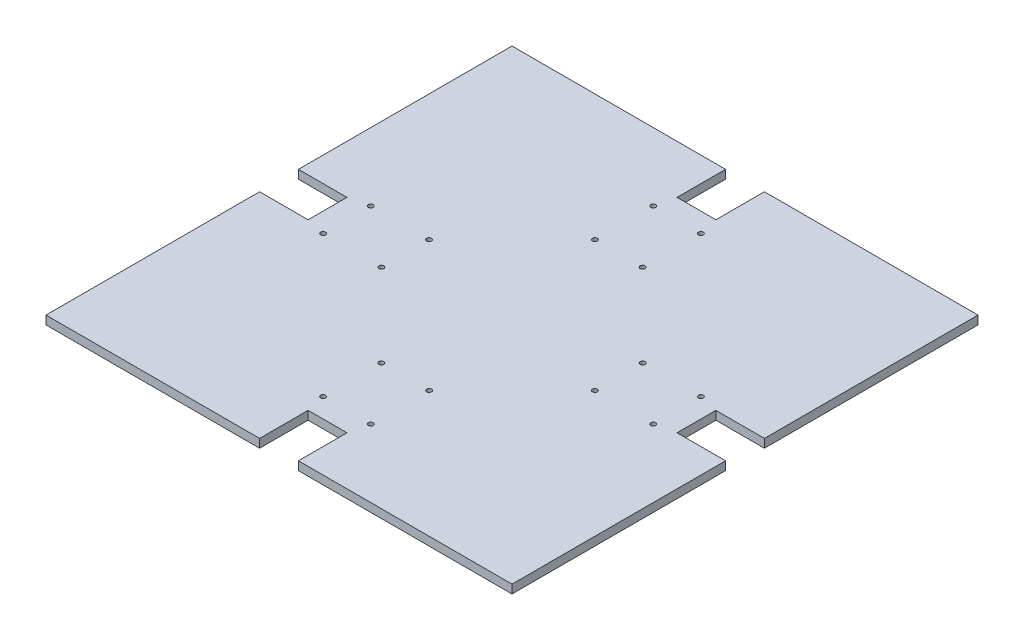
SolidWorks part; units mm, degrees
ref_plane "Front Plane" through (0, 0, 0) normal (0, 0, 1) x (1, 0, 0)
ref_plane "Top Plane" through (0, 0, 0) normal (0, 1, 0) x (1, 0, 0)
ref_plane "Right Plane" through (0, 0, 0) normal (1, 0, 0) x (0, 0, -1)
sketch "Sketch1" plane through (0, 0, 0) normal (0, 1, 0) x (1, 0, 0)
  line L0 (0, 152.4) -> (152.4, 0) construction
  line L1 (-152.4, 152.4) -> (152.4, 152.4)
  line L2 (-152.4, 152.4) -> (-152.4, -152.4)
  line L3 (-152.4, -152.4) -> (152.4, -152.4)
  line L4 (152.4, 152.4) -> (152.4, -152.4)
  line L5 (-152.4, 152.4) -> (152.4, -152.4) construction
  line L6 (-152.4, -152.4) -> (152.4, 152.4) construction
  line L7 (152.4, 0) -> (0, -152.4) construction
  line L8 (0, -152.4) -> (-152.4, 0) construction
  line L9 (-152.4, 0) -> (0, 152.4) construction
  point P0 (0, 0)
  dimension "D1" = 304.8
  dimension "D2" = 304.8
  dimension "D3" = 215.5261
extrude "Boss-Extrude1" add sketch "Sketch1" along normal blind 5.588
sketch "Sketch2" plane through (0, 5.588, 0) normal (0, 1, 0) x (1, 0, 0)
  line L0 (0, 152.4) -> (0, -152.4) construction
  line L1 (-107.95, 15.6) -> (-69.85, 15.6) construction
  line L2 (-107.95, 15.6) -> (-107.95, -15.6) construction
  line L3 (-107.95, -15.6) -> (-69.85, -15.6) construction
  line L4 (-69.85, 15.6) -> (-69.85, -15.6) construction
  line L5 (-107.95, 15.6) -> (-69.85, -15.6) construction
  line L6 (-107.95, -15.6) -> (-69.85, 15.6) construction
  line L7 (-15.6, 107.95) -> (15.6, 107.95) construction
  line L8 (-15.6, 107.95) -> (-15.6, 69.85) construction
  line L9 (-15.6, 69.85) -> (15.6, 69.85) construction
  line L10 (15.6, 107.95) -> (15.6, 69.85) construction
  line L11 (-15.6, 107.95) -> (15.6, 69.85) construction
  line L12 (-15.6, 69.85) -> (15.6, 107.95) construction
  line L13 (-15.6, -69.85) -> (15.6, -69.85) construction
  line L14 (-15.6, -69.85) -> (-15.6, -107.95) construction
  line L15 (-15.6, -107.95) -> (15.6, -107.95) construction
  line L16 (15.6, -69.85) -> (15.6, -107.95) construction
  line L17 (-15.6, -69.85) -> (15.6, -107.95) construction
  line L18 (-15.6, -107.95) -> (15.6, -69.85) construction
  line L19 (69.85, 15.6) -> (107.95, 15.6) construction
  line L20 (69.85, 15.6) -> (69.85, -15.6) construction
  line L21 (69.85, -15.6) -> (107.95, -15.6) construction
  line L22 (107.95, 15.6) -> (107.95, -15.6) construction
  line L23 (69.85, 15.6) -> (107.95, -15.6) construction
  line L24 (69.85, -15.6) -> (107.95, 15.6) construction
  line L25 (152.4, 152.4) -> (-152.4, 152.4) construction
  line L26 (-152.4, -152.4) -> (152.4, -152.4) construction
  line L28 (-152.4, 152.4) -> (-152.4, -152.4) construction
  line L29 (-152.4, 0) -> (152.4, 0) construction
  line L30 (152.4, -152.4) -> (152.4, 152.4) construction
  line L31 (-152.4, -12.7) -> (-120.65, -12.7)
  line L32 (-152.4, -12.7) -> (-152.4, 12.7)
  line L33 (-152.4, 12.7) -> (-120.65, 12.7)
  line L34 (-120.65, -12.7) -> (-120.65, 12.7)
  line L35 (-152.4, -12.7) -> (-120.65, 12.7) construction
  line L36 (-152.4, 12.7) -> (-120.65, -12.7) construction
  line L37 (-12.7, 120.65) -> (12.7, 120.65)
  line L38 (-12.7, 120.65) -> (-12.7, 152.4)
  line L39 (-12.7, 152.4) -> (12.7, 152.4)
  line L40 (12.7, 120.65) -> (12.7, 152.4)
  line L41 (-12.7, 120.65) -> (12.7, 152.4) construction
  line L42 (-12.7, 152.4) -> (12.7, 120.65) construction
  line L43 (120.65, -12.7) -> (152.4, -12.7)
  line L44 (120.65, -12.7) -> (120.65, 12.7)
  line L45 (120.65, 12.7) -> (152.4, 12.7)
  line L46 (152.4, -12.7) -> (152.4, 12.7)
  line L47 (120.65, -12.7) -> (152.4, 12.7) construction
  line L48 (120.65, 12.7) -> (152.4, -12.7) construction
  line L49 (-12.7, -152.4) -> (12.7, -152.4)
  line L50 (-12.7, -152.4) -> (-12.7, -120.65)
  line L51 (-12.7, -120.65) -> (12.7, -120.65)
  line L52 (12.7, -152.4) -> (12.7, -120.65)
  line L53 (-12.7, -152.4) -> (12.7, -120.65) construction
  line L54 (-12.7, -120.65) -> (12.7, -152.4) construction
  circle A0 centre (-107.95, 15.6) radius 1.6
  circle A1 centre (-69.85, 15.6) radius 1.6
  circle A2 centre (-107.95, -15.6) radius 1.6
  circle A3 centre (-69.85, -15.6) radius 1.6
  circle A4 centre (-15.6, -69.85) radius 1.6
  circle A5 centre (15.6, -69.85) radius 1.6
  circle A6 centre (-15.6, -107.95) radius 1.6
  circle A7 centre (15.6, -107.95) radius 1.6
  circle A8 centre (69.85, -15.6) radius 1.6
  circle A9 centre (69.85, 15.6) radius 1.6
  circle A10 centre (107.95, 15.6) radius 1.6
  circle A11 centre (107.95, -15.6) radius 1.6
  circle A12 centre (-15.6, 69.85) radius 1.6
  circle A13 centre (-15.6, 107.95) radius 1.6
  circle A14 centre (15.6, 107.95) radius 1.6
  circle A15 centre (15.6, 69.85) radius 1.6
  point P0 (-88.9, 0)
  point P5 (0, 88.9)
  point P10 (0, -88.9)
  point P15 (88.9, 0)
  point P48 (-136.525, 0)
  point P53 (0, 136.525)
  point P58 (136.525, 0)
  point P63 (0, -136.525)
  dimension "D1" = 3.2
  dimension "D2" = 38.1
  dimension "D3" = 31.2
  dimension "D4" = 25.4
  dimension "D5" = 31.75
extrude "Cut-Extrude1" cut sketch "Sketch2" against normal through all
